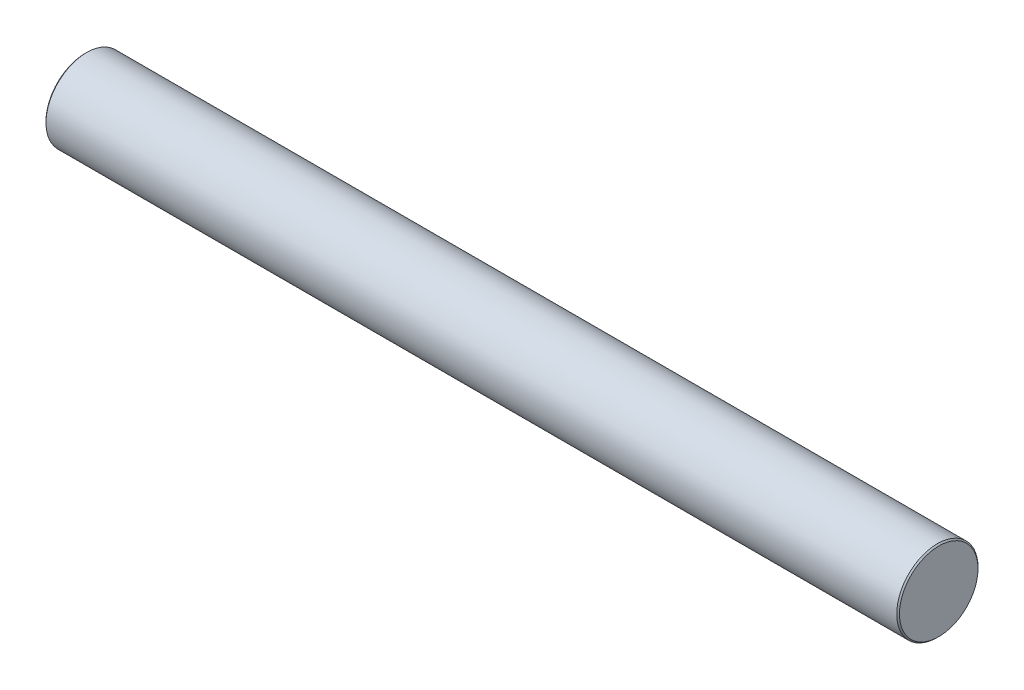
SolidWorks part; units mm, degrees
material "1.0402 (C22)"
ref_plane "Front Plane" through (0, 0, 0) normal (0, 0, 1) x (1, 0, 0)
ref_plane "Top Plane" through (0, 0, 0) normal (0, 1, 0) x (1, 0, 0)
ref_plane "Right Plane" through (0, 0, 0) normal (1, 0, 0) x (0, 0, -1)
sketch "Sketch1" plane through (0, 0, 0) normal (0, 0, 1) x (1, 0, 0)
  line L0 (-31.5, 0) -> (31.5, 0)
  line L2 (-31.5, 0) -> (-31.5, 3)
  line L3 (-31.5, 3) -> (31.5, 3)
  line L4 (31.5, -3) -> (31.5, 3)
  line L5 (0, 3) -> (0, 0) construction
  line L6 (-31.5, 0) -> (31.5, 0) construction
  line L7 (-18.8524, 0) -> (-46.8976, 0) construction
  point P0 (0, 0)
  dimension "D1" = 3
  dimension "D2" = 63
revolve "Revolve1" add sketch "Sketch1" angle 360 about L7
chamfer "Chamfer1" distance 0.1 angle 45 2 edges at (-31.5, 3, 0) (31.5, 3, 0)
